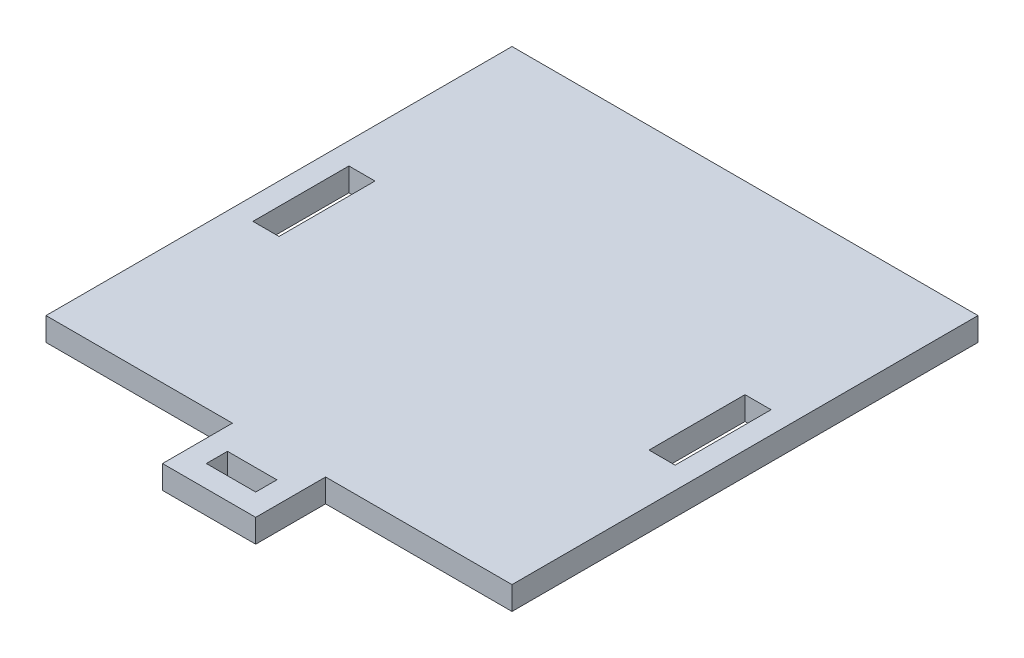
SolidWorks part; units mm, degrees
ref_plane "Спереди" through (0, 0, 0) normal (0, 0, 1) x (1, 0, 0)
ref_plane "Сверху" through (0, 0, 0) normal (0, 1, 0) x (1, 0, 0)
ref_plane "Справа" through (0, 0, 0) normal (1, 0, 0) x (0, 0, -1)
sketch "Sketch1" plane through (0, 0, 0) normal (0, 1, 0) x (1, 0, 0)
  line L0 (50, 0) -> (50, -72.2976) construction
  line L1 (0, 0) -> (100, 0)
  line L2 (0, 0) -> (0, -100)
  line L3 (0, -100) -> (40, -100)
  line L4 (100, 0) -> (100, -100)
  line L13 (60, -100) -> (100, -100)
  line L15 (40, -100) -> (40, -115)
  line L16 (40, -115) -> (60, -115)
  line L17 (60, -100) -> (60, -115)
  line L22 (4.7, -39.7) -> (4.7, -60.3)
  line L23 (4.7, -60.3) -> (10.3, -60.3)
  line L24 (10.3, -39.7) -> (10.3, -60.3)
  line L25 (4.7, -39.7) -> (10.3, -39.7)
  line L26 (95.3, -60.3) -> (89.7, -60.3)
  line L27 (89.7, -39.7) -> (89.7, -60.3)
  line L28 (95.3, -39.7) -> (89.7, -39.7)
  line L29 (95.3, -39.7) -> (95.3, -60.3)
  line L30 (44.7, -105.757) -> (44.7, -110.3)
  line L31 (44.7, -110.3) -> (55.3, -110.3)
  line L32 (55.3, -105.757) -> (55.3, -110.3)
  line L33 (44.7, -105.757) -> (55.3, -105.757)
  dimension "D1" = 100
  dimension "D2" = 100
  dimension "D7" = 20
  dimension "D8" = 15
  dimension "D9" = 40
extrude "Boss-Extrude1" add sketch "Sketch1" along normal blind 5
